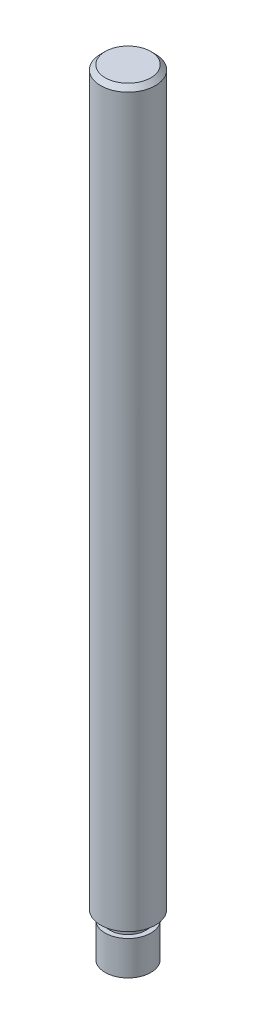
SolidWorks part; units mm, degrees
ref_plane "Front Plane" through (0, 0, 0) normal (0, 0, 1) x (1, 0, 0)
ref_plane "Top Plane" through (0, 0, 0) normal (0, 1, 0) x (1, 0, 0)
ref_plane "Right Plane" through (0, 0, 0) normal (1, 0, 0) x (0, 0, -1)
sketch "Sketch1" plane through (0, 0, 0) normal (0, 0, 1) x (1, 0, 0)
  line L0 (0, 0) -> (0, 117.9125) construction
  line L1 (0, 0) -> (5, 0)
  line L2 (3.95, 9.5) -> (3.95, 7.5)
  line L3 (3.95, 9.5) -> (6, 9.5)
  line L4 (6, 9.5) -> (6, 170)
  line L5 (6, 170) -> (0, 170)
  line L6 (0, 0) -> (0, 170)
  line L7 (3.95, 7.5) -> (5, 7.5)
  line L8 (5, 7.5) -> (5, 0)
  dimension "D1" = 9.5
  dimension "D2" = 12
  dimension "D3" = 2
  dimension "D4" = 160.5
  dimension "D5" = 5
  dimension "D6" = 3.95
revolve "Revolve1" add sketch "Sketch1" angle 360 about L0
chamfer "Chamfer1" distance 1 angle 45 1 edges at (0, 170, -6)
